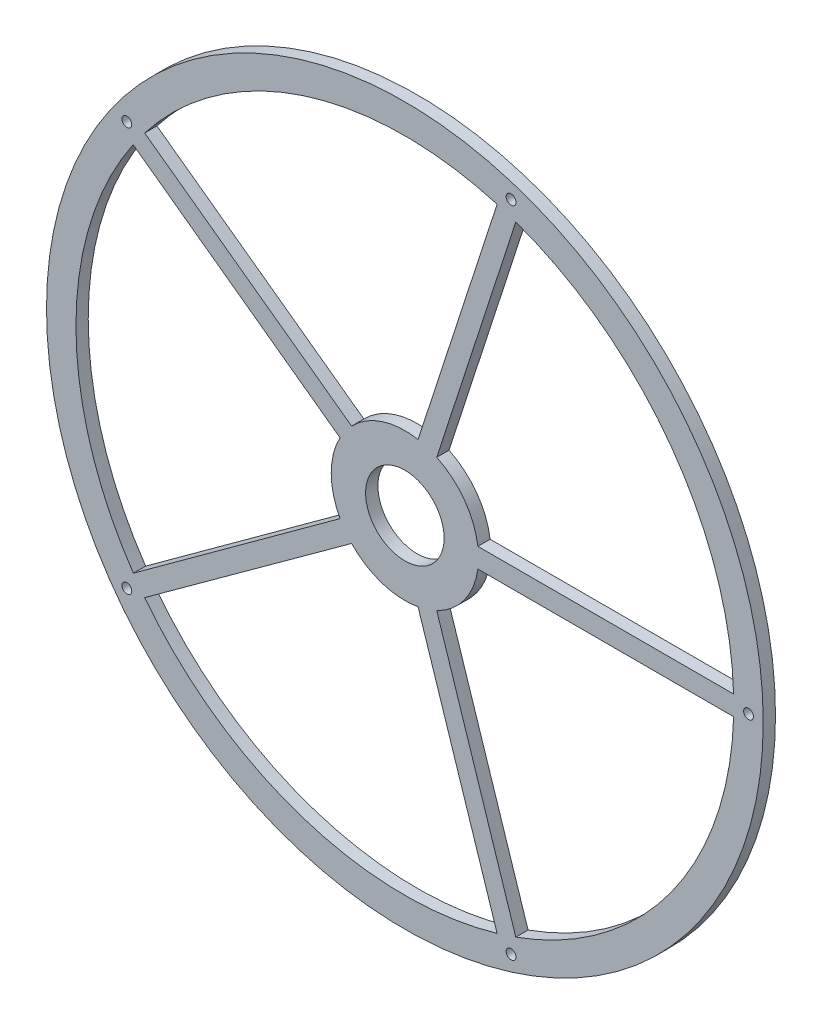
SolidWorks part; units mm, degrees
ref_plane "前视基准面" through (0, 0, 0) normal (0, 0, 1) x (1, 0, 0)
ref_plane "上视基准面" through (0, 0, 0) normal (0, 1, 0) x (1, 0, 0)
ref_plane "右视基准面" through (0, 0, 0) normal (1, 0, 0) x (0, 0, -1)
other "Configuration Table"
sketch "草图3" plane through (0, 0, 0) normal (0, 0, 1) x (1, 0, 0)
  circle A0 centre (0, 0) radius 73
extrude "凸台-拉伸3" add sketch "草图3" along normal blind 2.5
sketch "草图5" plane through (0, 0, 2.5) normal (0, 0, 1) x (1, 0, 0)
  circle A0 centre (0, 0) radius 67
extrude "切除-拉伸1" cut sketch "草图5" against normal blind 2.5
sketch "草图6" plane through (0, 0, 2.5) normal (0, 0, 1) x (1, 0, 0)
  circle A0 centre (0, 0) radius 15
extrude "凸台-拉伸4" add sketch "草图6" against normal blind 2.5 separate body
sketch "草图7" plane through (0, 0, 2.5) normal (0, 0, 1) x (1, 0, 0)
  circle A0 centre (0, 0) radius 8
extrude "切除-拉伸2" cut sketch "草图7" against normal blind 2.5
sketch "草图9" plane through (0, 0, 2.5) normal (0, 0, 1) x (1, 0, 0)
  line L0 (0, 0) -> (0, 2)
  line L1 (0, 2) -> (66.9701, 2)
  line L2 (0, 0) -> (0, -2)
  line L3 (0, -2) -> (66.9701, -2)
  line L4 (0, -2) -> (0, 2)
  circle A0 centre (0, 0) radius 67 construction
  arc A1 (66.9701, 2) -> (66.9701, -2) centre (0, 0) cw
  circle M1 centre (0, 0) radius 67
extrude "凸台-拉伸6" add sketch "草图9" against normal blind 2.5 contours L2 L3 L1 L0 M1
sketch "草图10" plane through (0, 0, 2.5) normal (0, 0, 1) x (1, 0, 0)
  line L0 (1.9021, -0.618) -> (0, 0)
  line L1 (0, 0) -> (-1.9021, 0.618)
  line L2 (1.9021, -0.618) -> (22.597, 63.0744)
  line L3 (-1.9021, 0.618) -> (18.7928, 64.3104)
  arc A0 (66.9701, 2) -> (66.9701, -2) centre (0, 0) ccw construction
  arc A1 (18.7928, 64.3104) -> (22.597, 63.0744) centre (0, 0) cw
extrude "凸台-拉伸7" add sketch "草图10" against normal blind 2.5
sketch "草图11" plane through (0, 0, 2.5) normal (0, 0, 1) x (1, 0, 0)
  line L1 (0, 0) -> (1.1756, 1.618)
  line L2 (0, 0) -> (-1.1756, -1.618)
  line L3 (-1.1756, -1.618) -> (-55.3556, 37.746)
  line L4 (1.1756, 1.618) -> (-53.0044, 40.9821)
  arc A0 (18.7928, 64.3104) -> (66.9701, -2) centre (0, 0) ccw construction
  arc A1 (-55.3556, 37.746) -> (-53.0044, 40.9821) centre (0, 0) cw
extrude "凸台-拉伸8" add sketch "草图11" against normal blind 2.5
sketch "草图12" plane through (0, 0, 2.5) normal (0, 0, 1) x (1, 0, 0)
  line L1 (0, 0) -> (1.1756, -1.618)
  line L2 (0, 0) -> (-1.1756, 1.618)
  line L3 (1.1756, -1.618) -> (-53.0044, -40.9821)
  line L4 (-1.1756, 1.618) -> (-55.303, -37.8229)
  arc A0 (-55.3556, 37.746) -> (66.9701, -2) centre (0, 0) ccw construction
  arc A1 (-55.303, -37.8229) -> (-53.0044, -40.9821) centre (0, 0) ccw
extrude "凸台-拉伸9" add sketch "草图12" against normal blind 2.5
sketch "草图13" plane through (0, 0, 2.5) normal (0, 0, 1) x (1, 0, 0)
  line L1 (0, 0) -> (1.9021, 0.618)
  line L2 (1.9021, 0.618) -> (22.597, -63.0744)
  line L3 (0, 0) -> (-1.9021, -0.618)
  line L4 (-1.9021, -0.618) -> (18.7928, -64.3104)
  arc A0 (-53.0044, -40.9821) -> (66.9701, -2) centre (0, 0) ccw construction
  arc A1 (22.597, -63.0744) -> (18.7928, -64.3104) centre (0, 0) cw
extrude "凸台-拉伸10" add sketch "草图13" against normal blind 2.5
sketch "草图14" plane through (0, 0, 2.5) normal (0, 0, 1) x (1, 0, 0)
  circle A0 centre (0, 0) radius 8
extrude "切除-拉伸3" cut sketch "草图14" against normal blind 2.5
sketch "草图15" plane through (0, 0, 2.5) normal (0, 0, 1) x (1, 0, 0)
  circle A0 centre (70, 0) radius 1
  circle A1 centre (21.6312, 66.574) radius 1
  circle A2 centre (-56.6312, 41.145) radius 1
  circle A3 centre (-56.6312, -41.145) radius 1
  circle A4 centre (21.6312, -66.574) radius 1
extrude "切除-拉伸4" cut sketch "草图15" against normal blind 2.5
